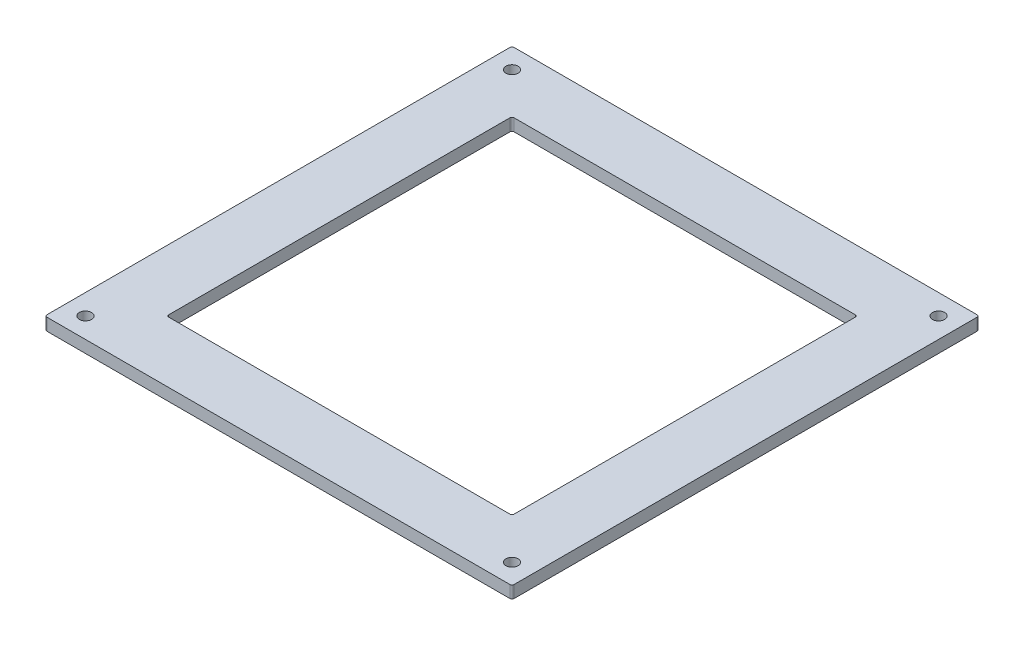
SolidWorks part; units mm, degrees
material "Beech"
ref_plane "Спереди" through (0, 0, 0) normal (0, 0, 1) x (1, 0, 0)
ref_plane "Сверху" through (0, 0, 0) normal (0, 1, 0) x (1, 0, 0)
ref_plane "Справа" through (0, 0, 0) normal (1, 0, 0) x (0, 0, -1)
sketch "Sketch1" plane through (0, 0, 0) normal (0, 1, 0) x (1, 0, 0)
  line L1 (0, 0) -> (230, 0)
  line L2 (0, 0) -> (0, 230)
  line L3 (0, 230) -> (230, 230)
  line L4 (230, 0) -> (230, 230)
  line L5 (30, 30) -> (200, 30)
  line L6 (30, 30) -> (30, 200)
  line L7 (30, 200) -> (200, 200)
  line L8 (200, 30) -> (200, 200)
  dimension "D1" = 230
  dimension "D2" = 230
  dimension "D3" = 30
  dimension "D4" = 30
  dimension "D5" = 30
  dimension "D6" = 30
extrude "border" add sketch "Sketch1" along normal blind 6
sketch "Sketch2" plane through (0, 6, 0) normal (0, 1, 0) x (1, 0, 0)
  line L0 (0, 230) -> (0, 0) construction
  line L1 (0, 0) -> (230, 0) construction
  circle A0 centre (10, 220) radius 3
  circle A1 centre (220, 220) radius 3
  circle A2 centre (220, 10) radius 3
  circle A3 centre (10, 10) radius 3
  point P8 (0, 115)
  point P9 (115, 0)
  dimension "D1" = 6
  dimension "D2" = 210
  dimension "D3" = 210
  dimension "D5" = 105
  dimension "D4" = 105
extrude "Cut-Extrude1" cut sketch "Sketch2" against normal through all
fillet "Fillet1" radius 1 8 edges at (230, 3, -230) (200, 3, -200) (200, 3, -30) (230, 3, 0) (30, 3, -30) (30, 3, -200) (0, 3, -230) (0, 3, 0)
